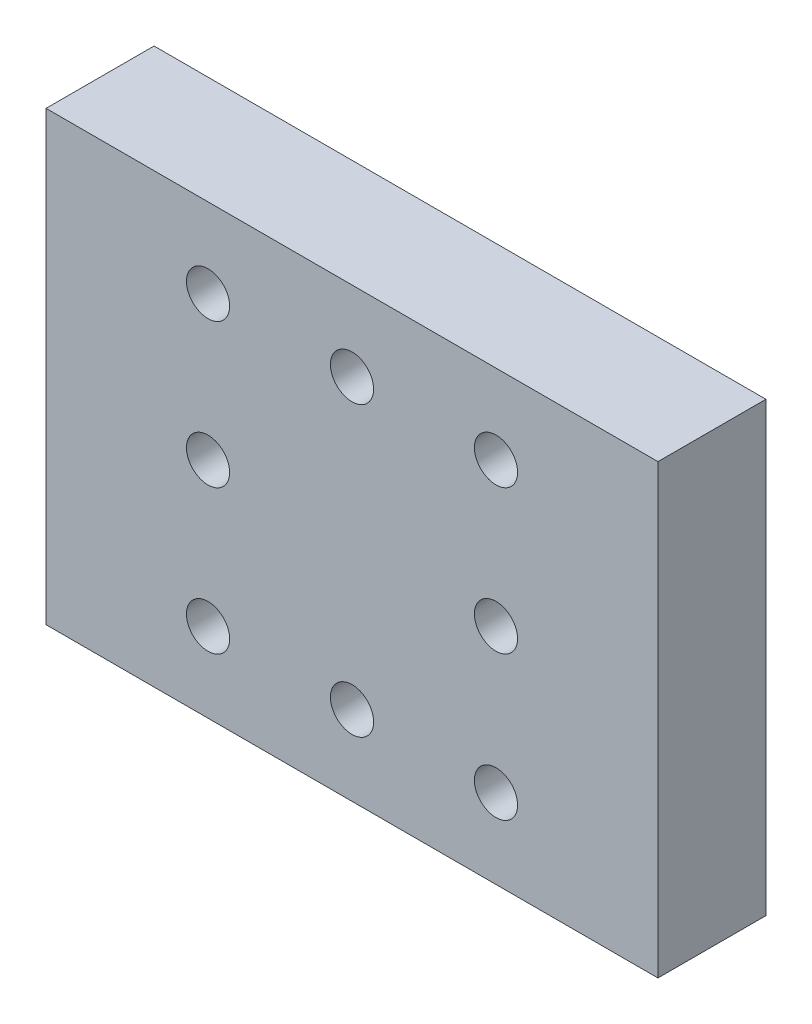
SolidWorks part; units mm, degrees
ref_plane "Plan de face" through (0, 0, 0) normal (0, 0, 1) x (1, 0, 0)
ref_plane "Plan de dessus" through (0, 0, 0) normal (0, 1, 0) x (1, 0, 0)
ref_plane "Plan de droite" through (0, 0, 0) normal (1, 0, 0) x (0, 0, -1)
sketch "Esquisse1" plane through (0, 0, 0) normal (0, 0, 1) x (1, 0, 0)
  line L1 (-17, 12.425) -> (17, 12.425)
  line L2 (-17, 12.425) -> (-17, -12.425)
  line L3 (-17, -12.425) -> (17, -12.425)
  line L4 (17, 12.425) -> (17, -12.425)
  line L5 (-17, 12.425) -> (17, -12.425) construction
  line L6 (-17, -12.425) -> (17, 12.425) construction
  point P0 (0, 0)
  dimension "D1" = 34
  dimension "D2" = 24.85
extrude "Boss.-Extru.1" add sketch "Esquisse1" along normal blind 6
sketch "Esquisse2" plane through (0, 0, 6) normal (0, 0, 1) x (1, 0, 0)
  line L0 (0, 124.25) -> (0, 210.9051) construction
  line L2 (-170, 0) -> (-244.4817, 0) construction
  line L4 (17, 12.425) -> (-17, 12.425) construction
  line L5 (-17, 12.425) -> (-17, -12.425) construction
  line L6 (17, -12.425) -> (17, 12.425) construction
  circle A0 centre (-8, 8.005) radius 1.2
  circle A1 centre (8, 8.005) radius 1.2
  circle A2 centre (0, 8.005) radius 1.2
  circle A3 centre (0, -8.005) radius 1.2
  circle A4 centre (8, -8.005) radius 1.2
  circle A5 centre (-8, -8.005) radius 1.2
  circle A6 centre (-8, 0) radius 1.2
  circle A7 centre (8, 0) radius 1.2
  dimension "D2" = 2.4
  dimension "D4" = 2.4
  dimension "D8" = 2.4
  dimension "D9" = 2.4
  dimension "D1" = 4.42
  dimension "D3" = 9
  dimension "D5" = 4.42
  dimension "D6" = 9
  dimension "D7" = 9
extrude "Enlèv. mat.-Extru.1" cut sketch "Esquisse2" against normal through all
